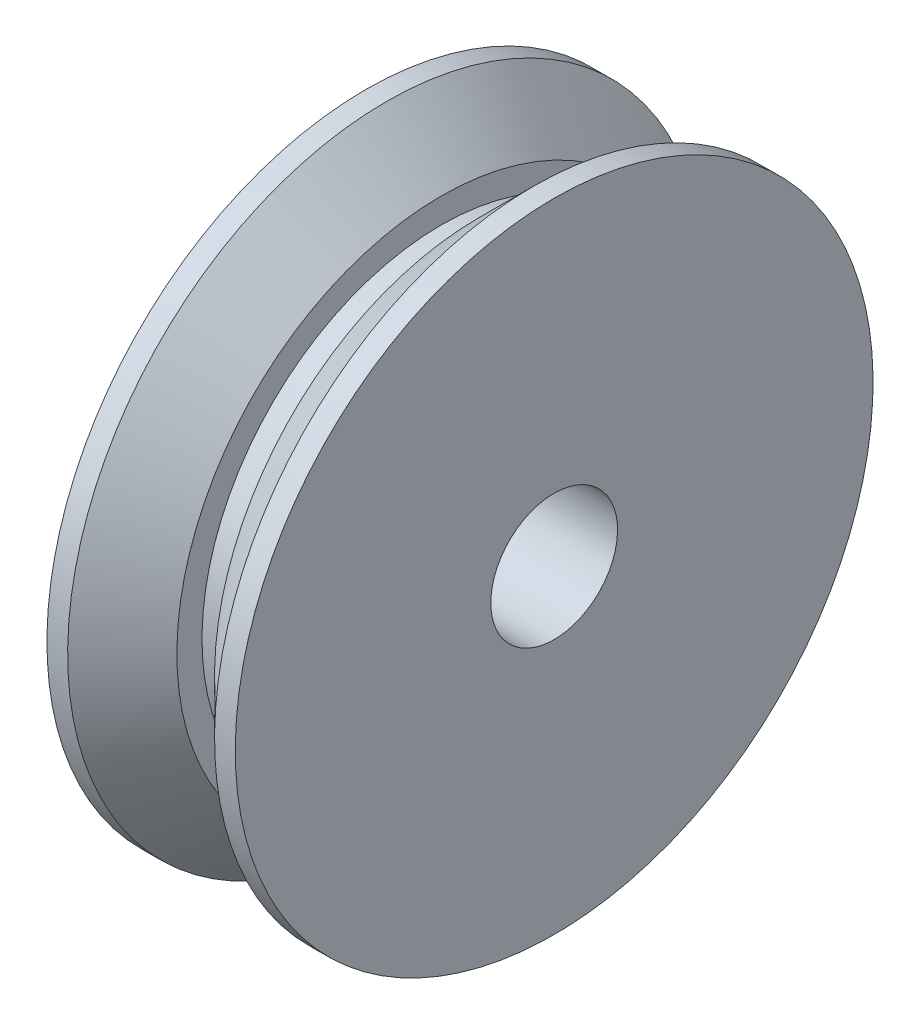
SolidWorks part; units mm, degrees
material "Barra Redonda SAE 1020 -  2\""
ref_plane "Plano frontal" through (0, 0, 0) normal (0, 0, 1) x (1, 0, 0)
ref_plane "Plano superior" through (0, 0, 0) normal (0, 1, 0) x (1, 0, 0)
ref_plane "Plano direito" through (0, 0, 0) normal (1, 0, 0) x (0, 0, -1)
sketch "Esboço1" plane through (0, 0, 0) normal (0, 0, 1) x (1, 0, 0)
  line L0 (5.85, -25.4) -> (1.5, -21.05)
  line L1 (0, 0) -> (-50.443, 0) construction
  line L2 (7.5, -5.05) -> (7.5, -25.4)
  line L3 (7.5, -25.4) -> (5.85, -25.4)
  line L4 (-7.5, -5.05) -> (-7.5, -25.4)
  line L5 (-1.5, -21.05) -> (-5.85, -25.4)
  line L6 (0, -35) -> (0, 0) construction
  line L7 (-1.5, -19.05) -> (1.5, -19.05)
  line L8 (-7.5, -5.05) -> (7.5, -5.05)
  line L9 (-5.85, -25.4) -> (-7.5, -25.4)
  line L10 (1.5, -19.05) -> (1.5, -21.05)
  line L11 (-1.5, -19.05) -> (-1.5, -21.05)
  dimension "D6" = 3
  dimension "D1" = 5.05
  dimension "D2" = 15
  dimension "D3" = 14
  dimension "D4" = 90
  dimension "D5" = 25.4
  dimension "D7" = 2
revolve "Revolução1" add sketch "Esboço1" angle 360 about L1
